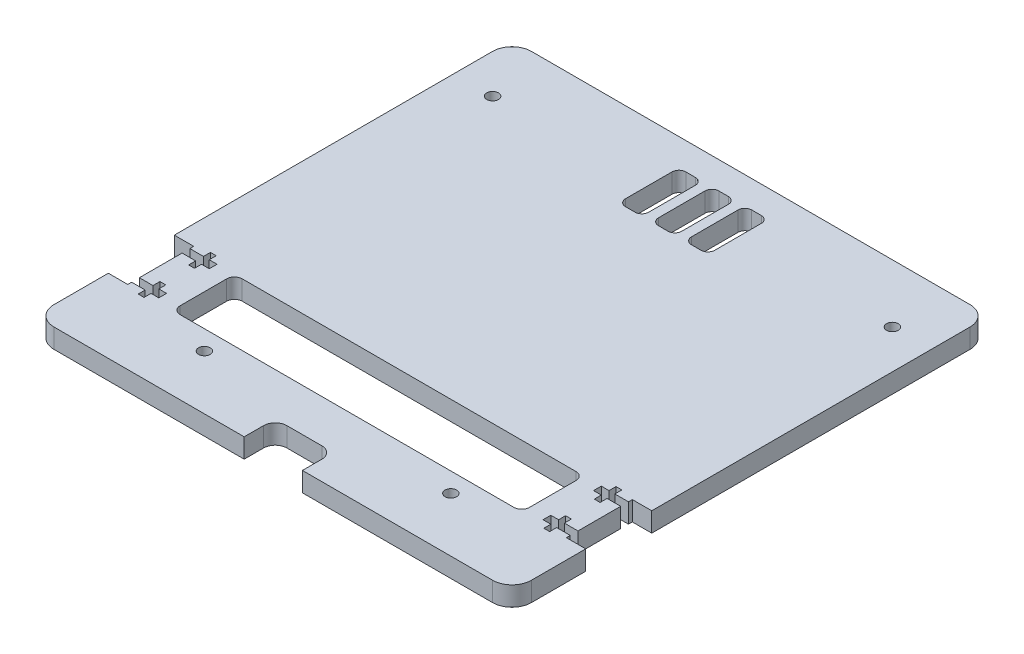
SolidWorks part; units mm, degrees
material "Acrílico (médio-alto impacto)"
ref_plane "Plano frontal" through (0, 0, 0) normal (0, 0, 1) x (1, 0, 0)
ref_plane "Plano superior" through (0, 0, 0) normal (0, 1, 0) x (1, 0, 0)
ref_plane "Plano direito" through (0, 0, 0) normal (1, 0, 0) x (0, 0, -1)
sketch "Esboço1" plane through (0, 0, 0) normal (0, 1, 0) x (1, 0, 0)
  line L1 (-56.5, -61.5) -> (56.5, -61.5)
  line L2 (-61.5, -56.5) -> (-61.5, 56.5)
  line L3 (-56.5, 61.5) -> (56.5, 61.5)
  line L4 (61.5, -56.5) -> (61.5, 56.5)
  arc A0 (61.5, -56.5) -> (56.5, -61.5) centre (56.5, -56.5) cw
  arc A1 (-56.5, -61.5) -> (-61.5, -56.5) centre (-56.5, -56.5) cw
  arc A2 (61.5, 56.5) -> (56.5, 61.5) centre (56.5, 56.5) ccw
  arc A3 (-56.5, 61.5) -> (-61.5, 56.5) centre (-56.5, 56.5) ccw
  point P0 (0, 0)
  dimension "D1" = 5
extrude "Ressalto-extrusão1" add sketch "Esboço1" along normal blind 5
sketch "Esboço2" plane through (0, 5, 0) normal (0, 1, 0) x (1, 0, 0)
  line L2 (56.5, 61.5) -> (-56.5, 61.5) construction
  line L3 (1.2331, 54.5) -> (-1.2331, 54.5)
  line L4 (3, 52.7331) -> (3, 40.7331)
  line L5 (1.2331, 38.9662) -> (-1.2331, 38.9662)
  line L6 (-3, 52.7331) -> (-3, 40.7331)
  line L7 (-61.5, 56.5) -> (-61.5, -56.5) construction
  line L9 (61.5, -56.5) -> (61.5, 56.5) construction
  line L11 (-7.2669, 54.5) -> (-9.7331, 54.5)
  line L12 (-5.5, 52.7331) -> (-5.5, 40.7331)
  line L13 (-7.2669, 38.9662) -> (-9.7331, 38.9662)
  line L14 (-11.5, 52.7331) -> (-11.5, 40.7331)
  line L15 (7.2669, 38.9662) -> (9.7331, 38.9662)
  line L16 (5.5, 40.7331) -> (5.5, 52.7331)
  line L17 (7.2669, 54.5) -> (9.7331, 54.5)
  line L18 (11.5, 40.7331) -> (11.5, 52.7331)
  arc A0 (-7.2669, 38.9662) -> (-5.5, 40.7331) centre (-7.2669, 40.7331) ccw
  arc A1 (-9.7331, 38.9662) -> (-11.5, 40.7331) centre (-9.7331, 40.7331) cw
  arc A2 (-11.5, 52.7331) -> (-9.7331, 54.5) centre (-9.7331, 52.7331) cw
  arc A3 (-7.2669, 54.5) -> (-5.5, 52.7331) centre (-7.2669, 52.7331) cw
  arc A4 (-3, 52.7331) -> (-1.2331, 54.5) centre (-1.2331, 52.7331) cw
  arc A5 (-1.2331, 38.9662) -> (-3, 40.7331) centre (-1.2331, 40.7331) cw
  arc A6 (3, 40.7331) -> (1.2331, 38.9662) centre (1.2331, 40.7331) cw
  arc A7 (1.2331, 54.5) -> (3, 52.7331) centre (1.2331, 52.7331) cw
  arc A8 (5.5, 52.7331) -> (7.2669, 54.5) centre (7.2669, 52.7331) cw
  arc A9 (7.2669, 38.9662) -> (5.5, 40.7331) centre (7.2669, 40.7331) cw
  arc A10 (9.7331, 38.9662) -> (11.5, 40.7331) centre (9.7331, 40.7331) ccw
  arc A11 (11.5, 52.7331) -> (9.7331, 54.5) centre (9.7331, 52.7331) ccw
  point P6 (0, 61.5)
  point P43 (-8.5, 54.5)
  dimension "D1" = 7
  dimension "D2" = 58.5
  dimension "D3" = 58.5
  dimension "D6" = 1.7669
  dimension "D4" = 2.5
  dimension "D5" = 2.5
  dimension "D7" = 7
  dimension "D8" = 7
extrude "Corte-extrusão1" cut sketch "Esboço2" against normal blind 5
sketch "Esboço3" plane through (0, 5, 0) normal (0, 1, 0) x (1, 0, 0)
  line L0 (-61.5, 56.5) -> (-61.5, -56.5) construction
  line L1 (-61.5, -42.5) -> (-56.5, -42.5)
  line L2 (-61.5, -42.5) -> (-61.5, -25.5)
  line L3 (-61.5, -25.5) -> (-56.5, -25.5)
  line L4 (-56.5, -42.5) -> (-56.5, -25.5)
  line L5 (-56.5, -61.5) -> (56.5, -61.5) construction
  line L6 (61.5, -56.5) -> (61.5, 56.5) construction
  line L7 (61.5, -42.5) -> (56.5, -42.5)
  line L8 (61.5, -42.5) -> (61.5, -25.5)
  line L9 (61.5, -25.5) -> (56.5, -25.5)
  line L10 (56.5, -42.5) -> (56.5, -25.5)
  dimension "D1" = 19
extrude "Corte-extrusão3" cut sketch "Esboço3" against normal blind 5
sketch "Esboço4" plane through (0, 5, 0) normal (0, 1, 0) x (1, 0, 0)
  line L0 (56.5, -25.5) -> (56.5, -42.5) construction
  line L1 (56.5, -41.5) -> (53, -41.5)
  line L2 (56.5, -41.5) -> (56.5, -39.5)
  line L3 (56.5, -39.5) -> (53, -39.5)
  line L4 (61.5, -25.5) -> (56.5, -25.5) construction
  line L5 (-56.5, -61.5) -> (56.5, -61.5) construction
  line L6 (53, -37.7) -> (51.5, -37.7)
  line L7 (53, -37.7) -> (53, -39.5)
  line L8 (53, -43.3) -> (51.5, -43.3)
  line L9 (51.5, -37.7) -> (51.5, -39.5)
  line L10 (53, -41.5) -> (53, -43.3)
  line L11 (56.5, -26.5) -> (53, -26.5)
  line L12 (51.5, -39.5) -> (49.5, -39.5)
  line L13 (53, -26.5) -> (53, -24.7)
  line L14 (51.5, -41.5) -> (49.5, -41.5)
  line L15 (49.5, -39.5) -> (49.5, -41.5)
  line L16 (51.5, -41.5) -> (51.5, -43.3)
  line L17 (56.5, -26.5) -> (56.5, -28.5)
  line L18 (56.5, -28.5) -> (53, -28.5)
  line L20 (51.5, -26.5) -> (51.5, -24.7)
  line L21 (51.5, -30.3) -> (53, -30.3)
  line L22 (51.5, -30.3) -> (51.5, -28.5)
  line L23 (51.5, -24.7) -> (53, -24.7)
  line L24 (53, -30.3) -> (53, -28.5)
  line L25 (51.5, -28.5) -> (49.5, -28.5)
  line L27 (51.5, -26.5) -> (49.5, -26.5)
  line L28 (49.5, -28.5) -> (49.5, -26.5)
  dimension "D1" = 20
  dimension "D2" = 1.8
  dimension "D3" = 1.8
  dimension "D4" = 3.5
  dimension "D5" = 1
  dimension "D6" = 1.8
  dimension "D7" = 1.8
extrude "Corte-extrusão4" cut sketch "Esboço4" against normal blind 10
mirror "Espelhar1" about plane through (0, 0, 0) normal (1, 0, 0) of "Corte-extrusão4"
sketch "Esboço5" plane through (0, 5, 0) normal (0, 1, 0) x (1, 0, 0)
  line L0 (-61.5, -42.5) -> (-61.5, -56.5) construction
  line L1 (43, -42.5) -> (-43, -42.5)
  line L2 (45, -40.5) -> (45, -28.5)
  line L3 (43, -26.5) -> (-43, -26.5)
  line L4 (-45, -40.5) -> (-45, -28.5)
  line L5 (61.5, -56.5) -> (61.5, -42.5) construction
  line L6 (-56.5, -61.5) -> (56.5, -61.5) construction
  arc A0 (45, -40.5) -> (43, -42.5) centre (43, -40.5) cw
  arc A1 (45, -28.5) -> (43, -26.5) centre (43, -28.5) ccw
  arc A2 (-43, -26.5) -> (-45, -28.5) centre (-43, -28.5) ccw
  arc A3 (-43, -42.5) -> (-45, -40.5) centre (-43, -40.5) cw
  point P14 (-61.5, -49.5)
  point P17 (61.5, -49.5)
  dimension "D1" = 2
  dimension "D2" = 16.5
  dimension "D3" = 16.5
  dimension "D4" = 19
extrude "Corte-extrusão5" cut sketch "Esboço5" against normal blind 5
sketch "Esboço6" plane through (0, 5, 0) normal (0, 1, 0) x (1, 0, 0)
  line L0 (56.5, 61.5) -> (-56.5, 61.5) construction
  line L1 (-61.5, 56.5) -> (-61.5, -25.5) construction
  line L2 (61.5, -25.5) -> (61.5, 56.5) construction
  line L3 (-56.5, -61.5) -> (56.5, -61.5) construction
  line L4 (-56.5, -61.5) -> (56.5, -61.5) construction
  line L5 (61.5, -56.5) -> (61.5, -42.5) construction
  line L6 (-61.5, -42.5) -> (-61.5, -56.5) construction
  circle A0 centre (-51.5, 46.5) radius 1.5
  circle A1 centre (51.5, 46.5) radius 1.5
  circle A2 centre (31.75, -47.5) radius 1.5
  circle A3 centre (-31.75, -47.5) radius 1.5
  point P17 (61.5, -49.5)
  dimension "D1" = 15
  dimension "D2" = 10
  dimension "D3" = 15
  dimension "D4" = 10
  dimension "D5" = 14
  dimension "D6" = 29.75
  dimension "D7" = 29.75
  dimension "D8" = 14
extrude "Corte-extrusão6" cut sketch "Esboço6" against normal blind 20
sketch "Esboço7" plane through (0, 0, 0) normal (0, -1, 0) x (1, 0, 0)
  line L0 (-56.5, 61.5) -> (56.5, 61.5) construction
  line L1 (7.5, 61.5) -> (-7.5, 61.5)
  line L2 (7.5, 61.5) -> (7.5, 56.5)
  line L3 (4.5, 53.5) -> (-4.5, 53.5)
  line L4 (-7.5, 61.5) -> (-7.5, 56.5)
  line L5 (61.5, 56.5) -> (61.5, 42.5) construction
  line L6 (-61.5, 42.5) -> (-61.5, 56.5) construction
  arc A0 (7.5, 56.5) -> (4.5, 53.5) centre (4.5, 56.5) cw
  arc A1 (-4.5, 53.5) -> (-7.5, 56.5) centre (-4.5, 56.5) cw
  dimension "D3" = 3
  dimension "D1" = 54
  dimension "D2" = 54
extrude "Corte-extrusão7" cut sketch "Esboço7" against normal blind 10
